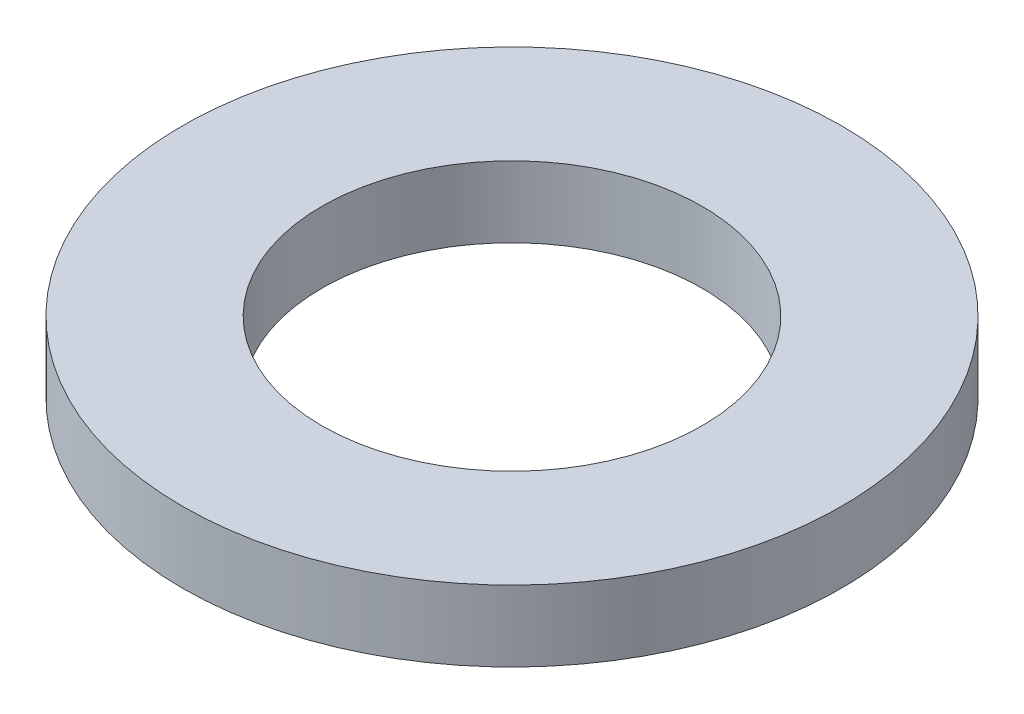
SolidWorks part; units mm, degrees
ref_plane "Front Plane" through (0, 0, 0) normal (0, 0, 1) x (1, 0, 0)
ref_plane "Top Plane" through (0, 0, 0) normal (0, 1, 0) x (1, 0, 0)
ref_plane "Right Plane" through (0, 0, 0) normal (1, 0, 0) x (0, 0, -1)
sketch "Sketch1" plane through (0, 0, 0) normal (0, 1, 0) x (1, 0, 0)
  circle A0 centre (0, 0) radius 8.255
  dimension "D1" = 16.51
extrude "Boss-Extrude1" add sketch "Sketch1" along normal blind 1.778
sketch "Sketch2" plane through (0, 1.778, 0) normal (0, 1, 0) x (1, 0, 0)
  circle A0 centre (0, 0) radius 4.7625
  dimension "D1" = 9.525
extrude "Cut-Extrude1" cut sketch "Sketch2" against normal up to surface (1.778 mm away) up to face at (0, 0, 8.255)
